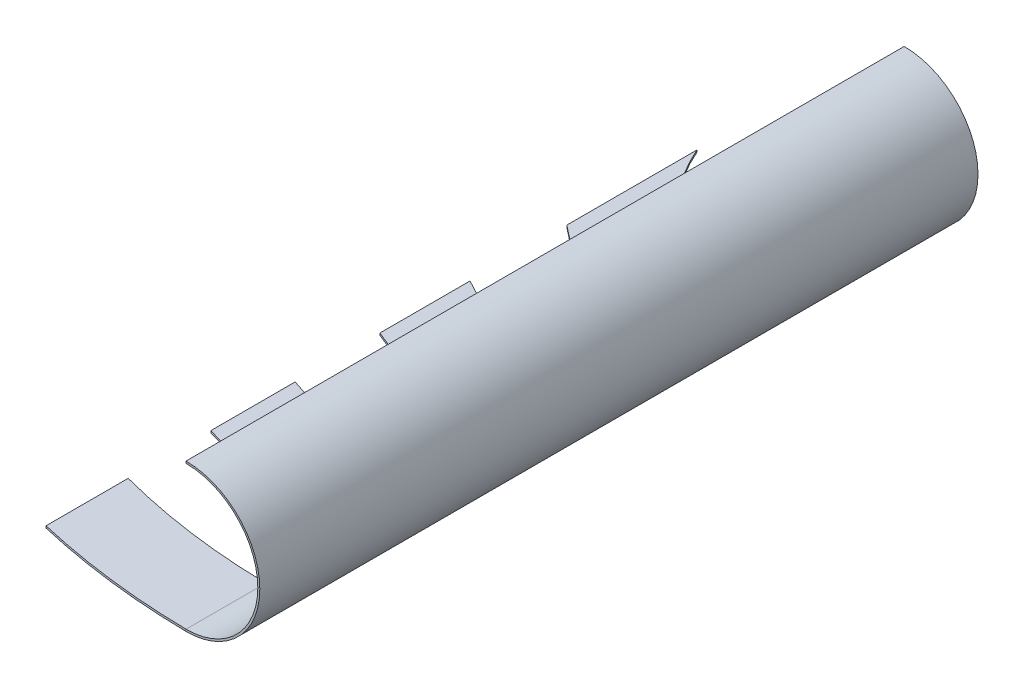
SolidWorks part; units mm, degrees
ref_plane "前视基准面" through (0, 0, 0) normal (0, 0, 1) x (1, 0, 0)
ref_plane "上视基准面" through (0, 0, 0) normal (0, 1, 0) x (1, 0, 0)
ref_plane "右视基准面" through (0, 0, 0) normal (1, 0, 0) x (0, 0, -1)
sketch "草图1" plane through (0, 0, 0) normal (0, 0, 1) x (1, 0, 0)
  circle A0 centre (0, 0) radius 18
  circle A1 centre (0, 0) radius 18.5
extrude "凸台-拉伸1" add sketch "草图1" along normal blind 180
sketch "草图2" plane through (0, 0, 0) normal (0, 0, -1) x (-1, 0, 0)
  line L0 (0, 0) -> (6.0887, 0)
  line L1 (0, 0) -> (0, 9.004)
sketch "草图3" plane through (0, 0, 180) normal (0, 0, 1) x (1, 0, 0)
  line L0 (0, 0) -> (-6.0887, 0)
  line L1 (0, 0) -> (0, 9.004)
ref_plane "基准面1" through (0, 0, 0) normal (1, 0, 0) x (0, 0, -1)
ref_plane "基准面2" through (0, 0, 0) normal (0, 1, 0) x (1, 0, 0)
sketch "草图6" plane through (0, 0, 0) normal (0, 0, -1) x (-1, 0, 0)
  circle A0 centre (0, 0) radius 18.5 construction
  point P0 (0, -18.5)
ref_point "点1"
ref_plane "基准面3" through (0, -18.5, 0) normal (0, 1, 0) x (1, 0, 0)
sketch "草图15" plane through (0, 0, 0) normal (0, 0, -1) x (-1, 0, 0)
  line L0 (0, 21.9854) -> (19.6473, 21.9854)
  line L1 (0, 21.9854) -> (0, -26.4376)
  line L2 (19.6473, 21.9854) -> (19.6473, -26.4376)
  line L3 (0, -26.4376) -> (19.6473, -26.4376)
  line L4 (0, 25.0366) -> (0, -25.0366) construction
extrude "切除-拉伸7" cut sketch "草图15" against normal mid plane 417
sketch "草图16" plane through (0, 0, 0) normal (1, 0, 0) x (0, 0, -1)
  line L0 (-80, -18.5) -> (-100, -18.5)
  line L1 (-180, -18.5) -> (0, -18.5) construction
  line L2 (-40, -18.5) -> (-60, -18.5)
  line L3 (-40, -18.5) -> (-40, -18)
  line L4 (-60, -18.5) -> (-60, -18)
  line L5 (-40, -18) -> (-60, -18)
  line L6 (-80, -18.5) -> (-80, -18)
  line L7 (-80, -18) -> (-100, -18)
  line L8 (-100, -18.5) -> (-100, -18)
  line L9 (-40, -18.5) -> (-80, -18.5) construction
  line L10 (-120, -18.5) -> (-140, -18.5)
  line L11 (-120, -18.5) -> (-120, -18)
  line L12 (-120, -18) -> (-140, -18)
  line L13 (-140, -18.5) -> (-140, -18)
  line L14 (-160, -18.5) -> (-180, -18.5)
  line L15 (-160, -18.5) -> (-160, -18)
  line L16 (-160, -18) -> (-180, -18)
  line L17 (-180, -18.5) -> (-180, -18)
  dimension "D1" = 4
  dimension "D2" = 20
  dimension "D3" = 0.5
  dimension "D4" = 40
extrude "凸台-拉伸4" add sketch "草图16" against normal blind 40
sketch "草图17" plane through (0, 0, 0) normal (1, 0, 0) x (0, 0, -1)
  line L0 (-100, -18.5) -> (-120, -18.5)
  line L1 (-140, -18.5) -> (-160, -18.5)
  line L6 (-60, -18.5) -> (-80, -18.5)
  line L7 (-60, -18.5) -> (-60, -17.5)
  line L8 (-80, -18.5) -> (-80, -17.5)
  line L9 (-60, -17.5) -> (-80, -17.5)
  line L10 (-80, -18.5) -> (-60, -18.5) construction
  line L11 (-100, -18.5) -> (-100, -17.5)
  line L12 (-100, -17.5) -> (-120, -17.5)
  line L13 (-120, -18.5) -> (-120, -17.5)
  line L14 (-60, -18.5) -> (-100, -18.5) construction
  line L15 (-140, -18.5) -> (-140, -17.5)
  line L16 (-140, -17.5) -> (-160, -17.5)
  line L17 (-160, -18.5) -> (-160, -17.5)
  dimension "D1" = 3
  dimension "D2" = 20
  dimension "D3" = 1
  dimension "D4" = 40
extrude "切除-拉伸8" cut sketch "草图17" along normal blind 40
sketch "草图20" plane through (0, -18.5, 0) normal (0, -1, 0) x (1, 0, 0)
  line L0 (0, 59.9528) -> (0, 39.9323)
  line L2 (-40, 68.8142) -> (-40, 91.1252)
  line L4 (-40, 11.916) -> (-40, 44.5562)
  line L6 (0, 180) -> (0, 159.99)
  line L7 (0, 99.9706) -> (0, 79.9808)
  line L8 (-40, 112.6284) -> (-40, 133.6863)
  line L9 (0, 139.9786) -> (0, 119.9752)
  line L10 (-40, 154.4833) -> (-40, 175.1021)
  arc A0 (0, 39.9323) -> (-40, 11.916) centre (2.5, -6.2) ccw
  arc A1 (0, 59.9528) -> (-40, 44.5562) centre (2.5, -6.2) ccw
  arc A2 (0, 79.9808) -> (-40, 68.8142) centre (2.5, -6.2) ccw
  arc A3 (0, 99.9706) -> (-40, 91.1252) centre (2.5, -6.2) ccw
  arc A4 (0, 119.9752) -> (-40, 112.6284) centre (2.5, -6.2) ccw
  arc A5 (0, 139.9786) -> (-40, 133.6863) centre (2.5, -6.2) ccw
  arc A6 (0, 159.99) -> (-40, 154.4833) centre (2.5, -6.2) ccw
  arc A7 (0, 180) -> (-40, 175.1021) centre (2.5, -6.2) ccw
extrude "凸台-拉伸8" add sketch "草图20" against normal blind 0.5
sketch "草图21" plane through (0, -18.5, 0) normal (0, -1, 0) x (1, 0, 0)
  line L0 (0, 79.9808) -> (0, 59.9528)
  line L1 (-40, 91.4051) -> (-40, 112.6284)
  line L3 (-40, 44.5562) -> (-40, 68.8142)
  line L5 (0, 159.99) -> (0, 140.0791)
  line L6 (0, 119.9752) -> (0, 100.2273)
  line L7 (-40, 133.7914) -> (-40, 154.4833)
  line L8 (-40, 175.0848) -> (-40, 180)
  line L9 (-40, 180) -> (-40, 184.5823)
  line L10 (-35.3294, 184.0453) -> (0, 179.9832)
  line L11 (-40, 184.5823) -> (-35.3294, 184.0453)
  arc A1 (0, 59.9528) -> (-40, 44.5562) centre (2.5, -6.2) ccw
  arc A2 (0, 79.9808) -> (-40, 68.8142) centre (2.5, -6.2) ccw
  arc A3 (0, 100.2273) -> (-40, 91.4051) centre (2.5, -6.2) ccw
  arc A4 (0, 119.9752) -> (-40, 112.6284) centre (2.5, -6.2) ccw
  arc A5 (0, 140.0791) -> (-40, 133.7914) centre (2.5, -6.2) ccw
  arc A6 (0, 159.99) -> (-40, 154.4833) centre (2.5, -6.2) ccw
  arc A7 (0, 179.9832) -> (-40, 175.0848) centre (2.5, -6.2) ccw
extrude "切除-拉伸10" cut sketch "草图21" against normal blind 0.5
ref_point "点2"
